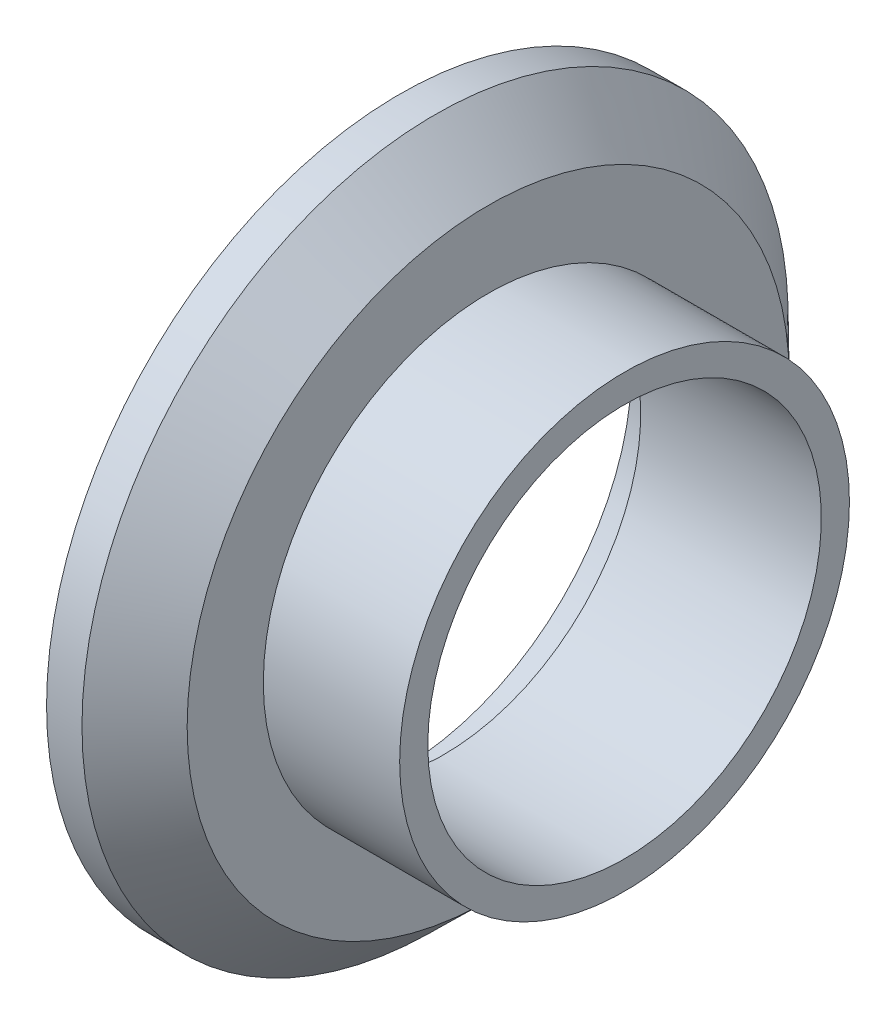
SolidWorks part; units mm, degrees
ref_plane "Front Plane" through (0, 0, 0) normal (0, 0, 1) x (1, 0, 0)
ref_plane "Top Plane" through (0, 0, 0) normal (0, 1, 0) x (1, 0, 0)
ref_plane "Right Plane" through (0, 0, 0) normal (1, 0, 0) x (0, 0, -1)
sketch "Axial profile (mm)" plane through (0, 0, 0) normal (0, 0, 1) x (1, 0, 0)
  line L0 (-110, 0) -> (75, 0) construction
  line L1 (3.5, 11.1125) -> (13.7, 11.1125)
  line L2 (13.7, 11.1125) -> (13.7, 12.7)
  line L3 (13.7, 12.7) -> (6, 12.7)
  line L4 (6, 12.7) -> (6, 17)
  line L5 (6, 17) -> (3, 19.94)
  line L6 (3, 19.94) -> (1, 19.94)
  line L7 (1, 19.94) -> (1, 13.1)
  line L8 (1, 13.1) -> (3.5, 13.1)
  line L9 (3.5, 13.1) -> (3.5, 11.1125)
revolve "Full revolution" add sketch "Axial profile (mm)" angle 360 about L0
